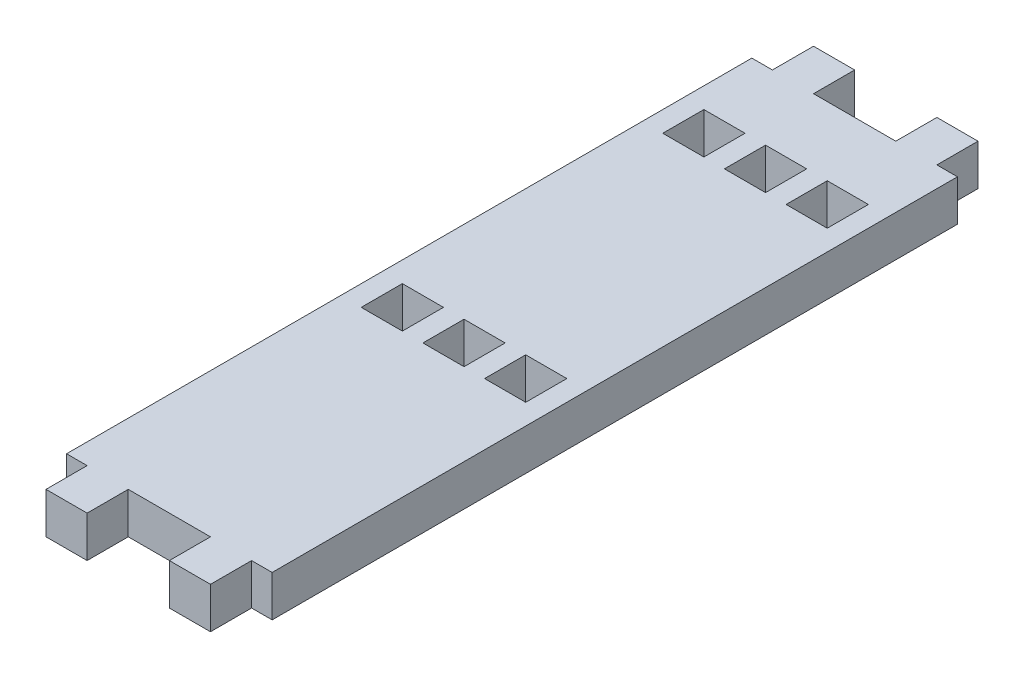
SolidWorks part; units mm, degrees
material "Maple"
ref_plane "Front Plane" through (0, 0, 0) normal (0, 0, 1) x (1, 0, 0)
ref_plane "Top Plane" through (0, 0, 0) normal (0, 1, 0) x (1, 0, 0)
ref_plane "Right Plane" through (0, 0, 0) normal (1, 0, 0) x (0, 0, -1)
sketch "Sketch1" plane through (0, 0, 0) normal (0, 1, 0) x (1, 0, 0)
  line L0 (0, 0) -> (-3, 0)
  line L1 (-30, 0) -> (-30, -100)
  line L2 (-30, -100) -> (-27, -100)
  line L3 (0, -100) -> (0, 0)
  line L4 (-18, -54) -> (-18, -60)
  line L5 (-18, -60) -> (-12, -60)
  line L6 (-12, -60) -> (-12, -54)
  line L7 (-12, -54) -> (-18, -54)
  line L8 (-9, -54) -> (-9, -60)
  line L9 (-9, -60) -> (-3, -60)
  line L10 (-3, -60) -> (-3, -54)
  line L11 (-3, -100) -> (-3, -106)
  line L12 (-27, -60) -> (-21, -60)
  line L13 (-21, -60) -> (-21, -54)
  line L14 (-21, -54) -> (-27, -54)
  line L15 (-27, -54) -> (-27, -60)
  line L16 (-3, -54) -> (-9, -54)
  line L17 (-18, -10) -> (-18, -16)
  line L18 (-18, -16) -> (-12, -16)
  line L19 (-12, -16) -> (-12, -10)
  line L20 (-12, -10) -> (-18, -10)
  line L21 (-9, -10) -> (-9, -16)
  line L22 (-9, -16) -> (-3, -16)
  line L23 (-3, -16) -> (-3, -10)
  line L24 (-27, -16) -> (-21, -16)
  line L25 (-21, -16) -> (-21, -10)
  line L26 (-21, -10) -> (-27, -10)
  line L27 (-27, -10) -> (-27, -16)
  line L28 (-3, -10) -> (-9, -10)
  line L29 (-3, -106) -> (-9, -106)
  line L30 (-9, -106) -> (-9, -100)
  line L31 (-3, -100) -> (0, -100)
  line L32 (-27, -100) -> (-27, -106)
  line L33 (-27, -106) -> (-21, -106)
  line L34 (-21, -106) -> (-21, -100)
  line L35 (-21, -100) -> (-9, -100)
  line L36 (-27, 0) -> (-27, 6)
  line L37 (-27, 6) -> (-21, 6)
  line L38 (-21, 6) -> (-21, 0)
  line L39 (-9, 0) -> (-9, 6)
  line L40 (-9, 6) -> (-3, 6)
  line L41 (-3, 6) -> (-3, 0)
  line L42 (-9, 0) -> (-21, 0)
  line L43 (-27, 0) -> (-30, 0)
  point P31 (-15, -10)
  dimension "D2" = 3
  dimension "D3" = 6
  dimension "D4" = 6
  dimension "D5" = 3
  dimension "D6" = 3
  dimension "D7" = 6
  dimension "D8" = 100
  dimension "D9" = 30
  dimension "D10" = 6
  dimension "D11" = 40
  dimension "D12" = 6
  dimension "D13" = 6
  dimension "D14" = 6
  dimension "D15" = 3
  dimension "D16" = 6
  dimension "D17" = 3
  dimension "D18" = 3
  dimension "D19" = 6
  dimension "D20" = 6
  dimension "D21" = 10
  dimension "D22" = 0
  dimension "D23" = 0
  dimension "D24" = 3
  dimension "D25" = 3
  dimension "D26" = 6
extrude "Boss-Extrude2" add sketch "Sketch1" along normal blind 6
